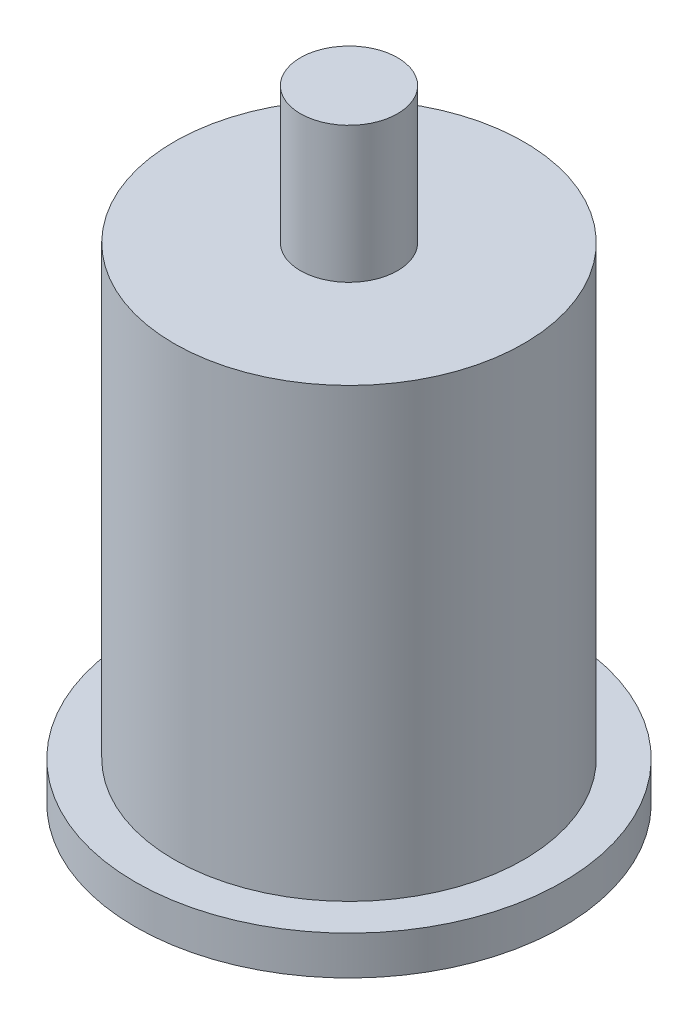
SolidWorks part; units mm, degrees
ref_plane "Front Plane" through (0, 0, 0) normal (0, 0, 1) x (1, 0, 0)
ref_plane "Top Plane" through (0, 0, 0) normal (0, 1, 0) x (1, 0, 0)
ref_plane "Right Plane" through (0, 0, 0) normal (1, 0, 0) x (0, 0, -1)
ref_plane "Plane1" through (0, -139.5, 0) normal (0, 1, 0) x (1, 0, 0)
sketch "Sketch1" plane through (0, -139.5, 0) normal (0, 1, 0) x (1, 0, 0)
  circle A0 centre (15, -26) radius 11
extrude "Boss-Extrude1" add sketch "Sketch1" along normal blind 2
ref_plane "Plane2" through (0, -137.5, 0) normal (0, 1, 0) x (1, 0, 0)
sketch "Sketch2" plane through (0, -137.5, 0) normal (0, 1, 0) x (1, 0, 0)
  circle A0 centre (15, -26) radius 9
extrude "Boss-Extrude2" add sketch "Sketch2" along normal blind 23
ref_plane "Plane3" through (0, -114.5, 0) normal (0, 1, 0) x (1, 0, 0)
sketch "Sketch3" plane through (0, -114.5, 0) normal (0, 1, 0) x (1, 0, 0)
  circle A0 centre (15, -26) radius 2.5
extrude "Boss-Extrude3" add sketch "Sketch3" along normal blind 7
